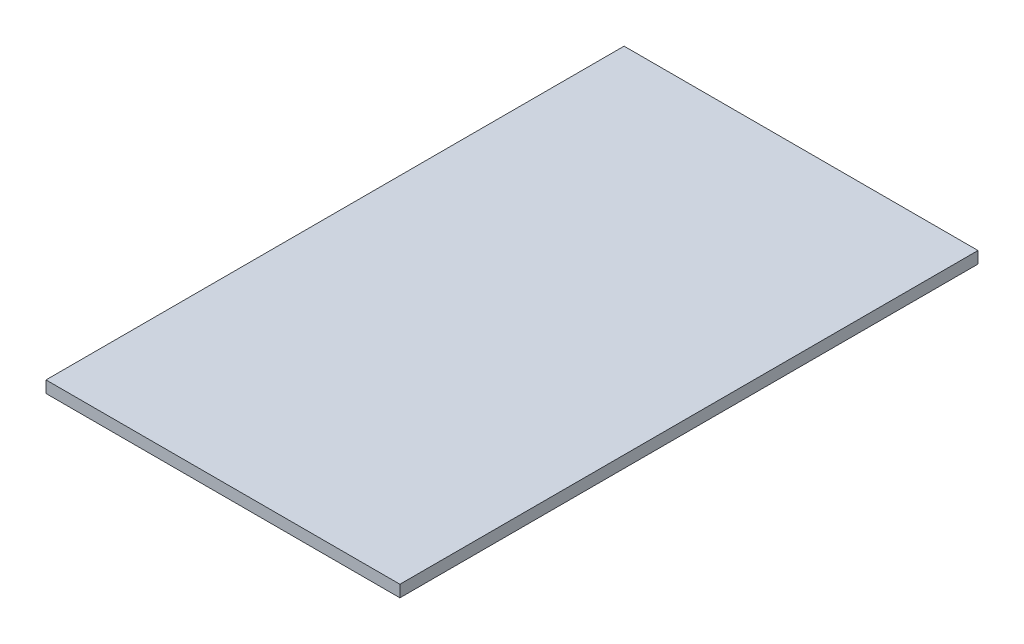
SolidWorks part; units mm, degrees
ref_plane "Front Plane" through (0, 0, 0) normal (0, 0, 1) x (1, 0, 0)
ref_plane "Top Plane" through (0, 0, 0) normal (0, 1, 0) x (1, 0, 0)
ref_plane "Right Plane" through (0, 0, 0) normal (1, 0, 0) x (0, 0, -1)
sketch "Sketch1" plane through (0, 0, 0) normal (0, 1, 0) x (1, 0, 0)
  line L1 (0, 0) -> (381, 0)
  line L2 (0, 0) -> (0, 622.3)
  line L3 (0, 622.3) -> (381, 622.3)
  line L4 (381, 0) -> (381, 622.3)
  dimension "D1" = 381
  dimension "D2" = 622.3
extrude "Boss-Extrude1" add sketch "Sketch1" along normal blind 12.7
